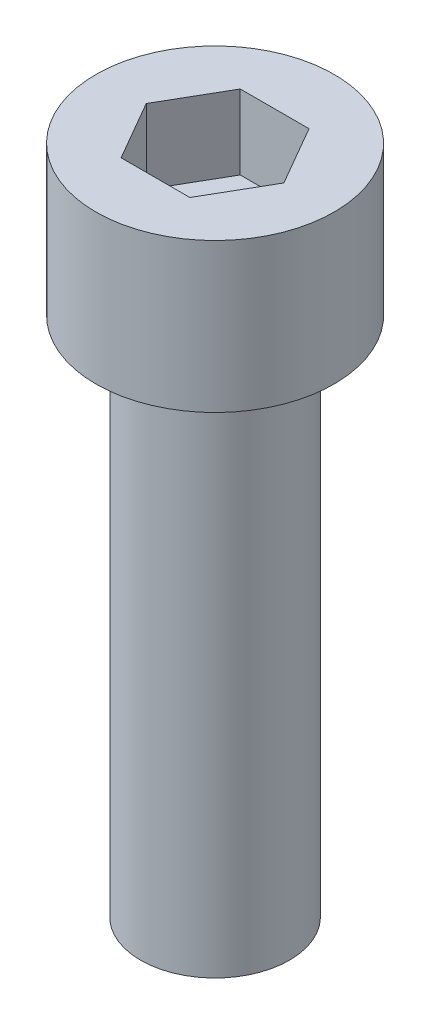
SolidWorks part; units mm, degrees
material "AISI 304"
ref_plane "Front Plane" through (0, 0, 0) normal (0, 0, 1) x (1, 0, 0)
ref_plane "Top Plane" through (0, 0, 0) normal (0, 1, 0) x (1, 0, 0)
ref_plane "Right Plane" through (0, 0, 0) normal (1, 0, 0) x (0, 0, -1)
sketch "Sketch1" plane through (0, 0, 0) normal (0, 0, 1) x (1, 0, 0)
  line L0 (0, 61.6916) -> (0, -59.3578) construction
  line L1 (0, -35) -> (5, -35)
  line L2 (5, -35) -> (5, 0)
  line L3 (5, 0) -> (8, 0)
  line L4 (8, 0) -> (8, 10)
  line L5 (8, 10) -> (0, 10)
  line L6 (0, 10) -> (0, -35)
  dimension "D1" = 35
  dimension "D2" = 16
  dimension "D3" = 10
  dimension "D4" = 10
revolve "Revolve1" add sketch "Sketch1" angle 360 about L0
sketch "Sketch2" plane through (0, 10, 0) normal (0, 1, 0) x (-1, 0, 0)
  line L1 (-2.3094, -4) -> (2.3094, -4)
  line L2 (2.3094, -4) -> (4.6188, 0)
  line L3 (4.6188, 0) -> (2.3094, 4)
  line L4 (2.3094, 4) -> (-2.3094, 4)
  line L5 (-2.3094, 4) -> (-4.6188, 0)
  line L6 (-4.6188, 0) -> (-2.3094, -4)
  circle A0 centre (0, 0) radius 4 construction
  dimension "D1" = 8
extrude "Cut-Extrude1" cut sketch "Sketch2" against normal blind 5
